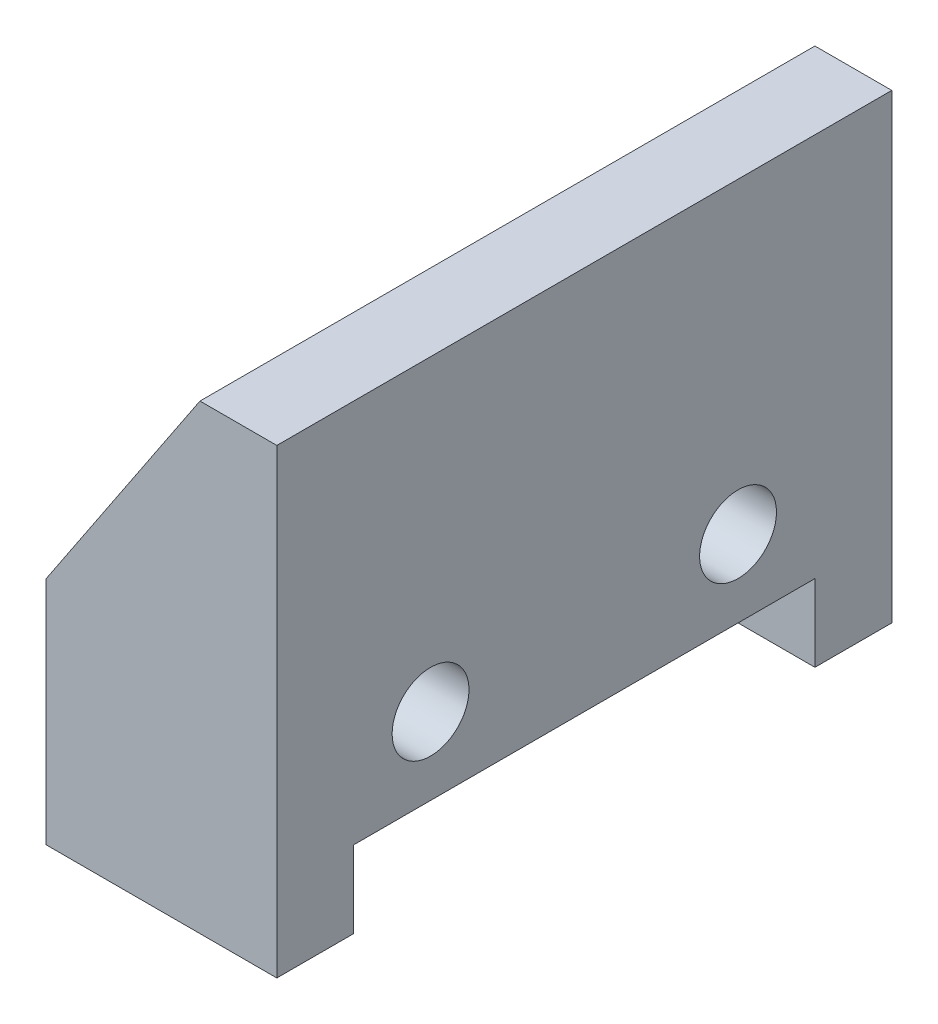
SolidWorks part; units mm, degrees
ref_plane "Front Plane" through (0, 0, 0) normal (0, 0, 1) x (1, 0, 0)
ref_plane "Top Plane" through (0, 0, 0) normal (0, 1, 0) x (1, 0, 0)
ref_plane "Right Plane" through (0, 0, 0) normal (1, 0, 0) x (0, 0, -1)
sketch "Sketch1" plane through (0, 0, 0) normal (0, 0, 1) x (1, 0, 0)
  line L1 (0, 0) -> (15, 0)
  line L2 (0, 0) -> (0, 15)
  line L4 (15, 0) -> (15, 30)
  line L6 (0, 15) -> (10, 30)
  line L7 (10, 30) -> (15, 30)
  dimension "D1" = 15
  dimension "D2" = 30
  dimension "D3" = 15
  dimension "D4" = 5
extrude "Boss-Extrude1" add sketch "Sketch1" along normal mid plane 40
sketch "Sketch2" plane through (15, 0, 0) normal (1, 0, 0) x (0, 0, -1)
  line L0 (0, 0) -> (0, 3.8125) construction
  line L1 (-20, 0) -> (20, 0) construction
  line L2 (-15, 0) -> (15, 0)
  line L3 (-15, 0) -> (-15, 5)
  line L4 (-15, 5) -> (15, 5)
  line L5 (15, 0) -> (15, 5)
  circle A1 centre (10, 10) radius 2.5
  circle A2 centre (-10, 10) radius 2.5
  point P13 (0, 5)
  dimension "D1" = 5
  dimension "D2" = 10
  dimension "D3" = 10
  dimension "D4" = 30
  dimension "D5" = 5
extrude "Cut-Extrude1" cut sketch "Sketch2" against normal through all
